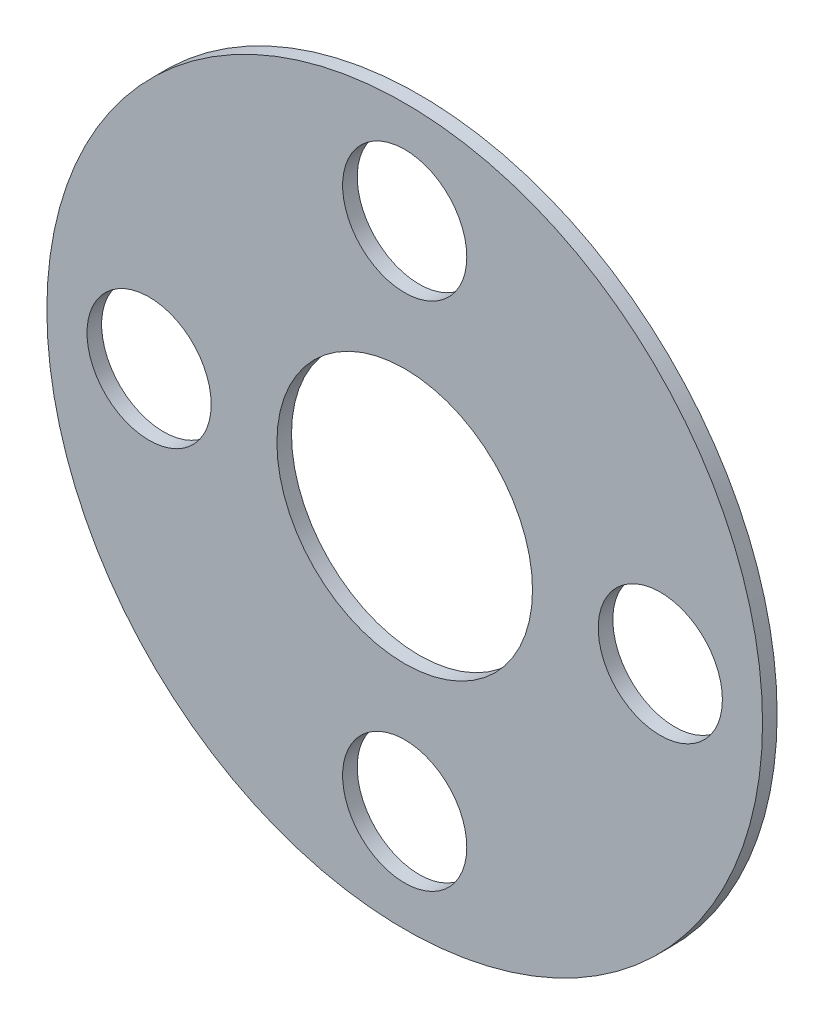
SolidWorks part; units mm, degrees
ref_plane "Front Plane" through (0, 0, 0) normal (0, 0, 1) x (1, 0, 0)
ref_plane "Top Plane" through (0, 0, 0) normal (0, 1, 0) x (1, 0, 0)
ref_plane "Right Plane" through (0, 0, 0) normal (1, 0, 0) x (0, 0, -1)
sketch "S_cyl1" plane through (0, 0, 0) normal (0, 0, 1) x (1, 0, 0)
  circle A0 centre (0, 0) radius 9.8
  dimension "D1_S_cyl1" = 19.6
extrude "Boss_1" add sketch "S_cyl1" along normal blind 0.4
ref_plane "PZ_m0_100" through (0, 0, -0.1) normal (0, 0, 1) x (1, 0, 0)
sketch "S_hole2" plane through (0, 0, -0.1) normal (0, 0, 1) x (1, 0, 0)
  circle A0 centre (0, 0) radius 3.5
  dimension "D1_S_hole2" = 7
extrude "Hole_2" cut sketch "S_hole2" along normal blind 0.6
sketch "S_hole3" plane through (0, 0, -0.1) normal (0, 0, 1) x (1, 0, 0)
  circle A0 centre (7, 0) radius 1.7
  dimension "D1_S_hole3" = 3.4
  dimension "P2" = 7
extrude "Hole_3" cut sketch "S_hole3" along normal blind 0.6
sketch "S_hole4" plane through (0, 0, -0.1) normal (0, 0, 1) x (1, 0, 0)
  circle A0 centre (0, 7) radius 1.7
  dimension "D1_S_hole4" = 3.4
  dimension "P2" = 7
extrude "Hole_4" cut sketch "S_hole4" along normal blind 0.6
sketch "S_hole5" plane through (0, 0, -0.1) normal (0, 0, 1) x (1, 0, 0)
  circle A0 centre (-7, 0) radius 1.7
  dimension "D1_S_hole5" = 3.4
  dimension "P2" = 7
extrude "Hole_5" cut sketch "S_hole5" along normal blind 0.6
sketch "S_hole6" plane through (0, 0, -0.1) normal (0, 0, 1) x (1, 0, 0)
  circle A0 centre (0, -7) radius 1.7
  dimension "D1_S_hole6" = 3.4
  dimension "P2" = 7
extrude "Hole_6" cut sketch "S_hole6" along normal blind 0.6
equation "\"plate_t\" = 3"
equation "\"clearance\" = 0.5"
